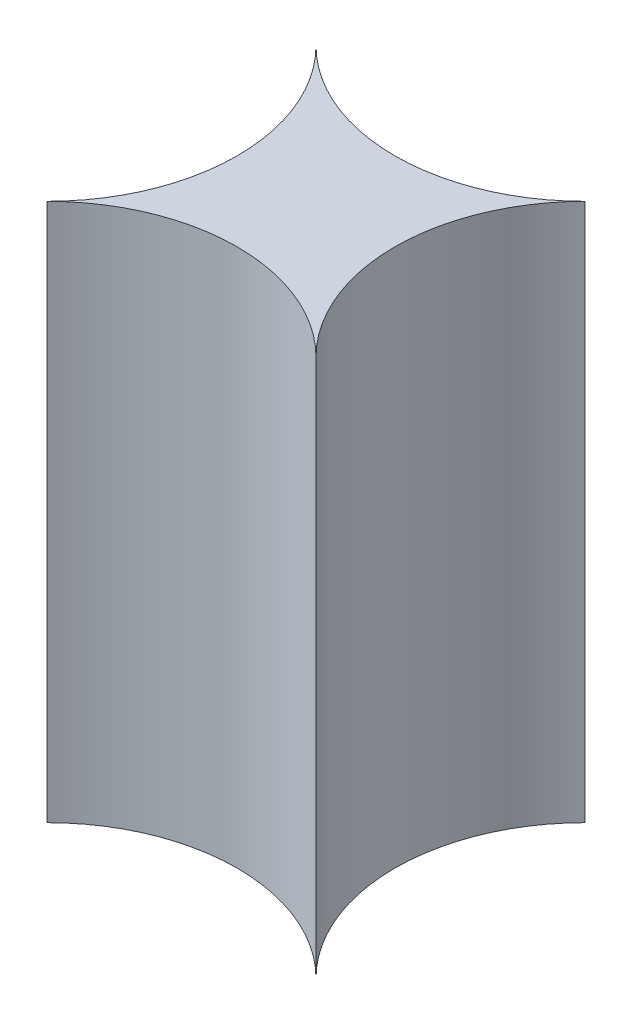
SolidWorks part; units mm, degrees
ref_plane "Front Plane" through (0, 0, 0) normal (0, 0, 1) x (1, 0, 0)
ref_plane "Top Plane" through (0, 0, 0) normal (0, 1, 0) x (1, 0, 0)
ref_plane "Right Plane" through (0, 0, 0) normal (1, 0, 0) x (0, 0, -1)
sketch "Sketch1" plane through (0, 0, 0) normal (0, 1, 0) x (1, 0, 0)
  line L5 (-2.5, -2.5) -> (2.5, 2.5) construction
  line L6 (-2.5, 2.5) -> (2.5, -2.5) construction
  arc A1 (-2.5, 2.5) -> (-2.5, -2.5) centre (-5, 0) cw
  circle A2 centre (0, 0) radius 3.5355 construction
  arc A5 (-2.5, 2.5) -> (2.5, 2.5) centre (0, 5) ccw
  arc A6 (2.5, 2.5) -> (2.5, -2.5) centre (5, 0) ccw
  arc A7 (-2.5, -2.5) -> (2.5, -2.5) centre (0, -5) cw
  point P0 (0, 0)
  dimension "D1" = 5
  dimension "D2" = 5
  dimension "D4" = 3.5355
extrude "Boss-Extrude1" add sketch "Sketch1" along normal blind 10 contours A6 A7 A1 A5
